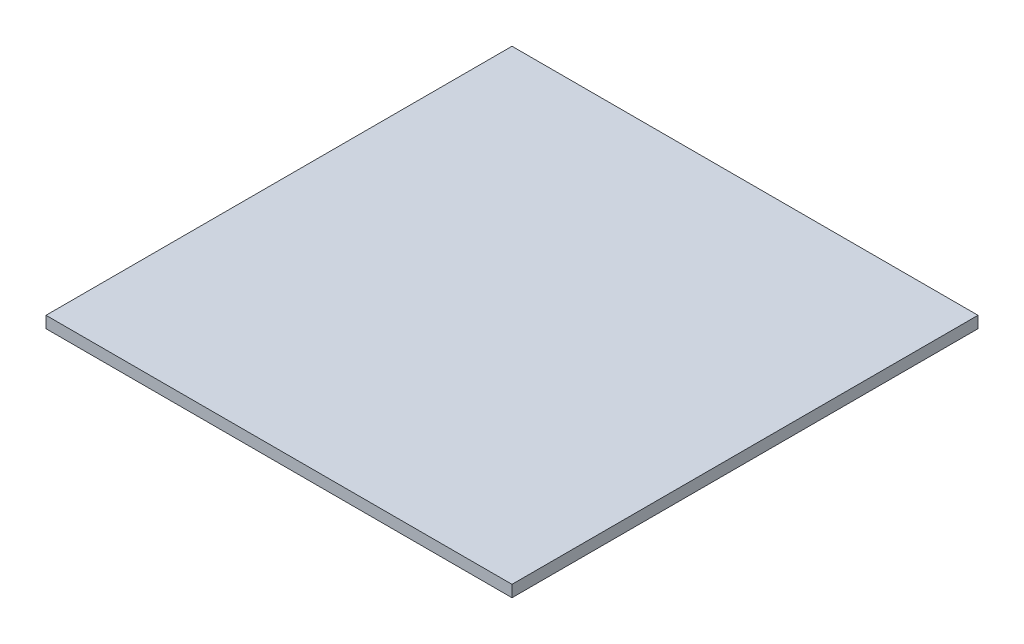
SolidWorks part; units mm, degrees
ref_plane "Front Plane" through (0, 0, 0) normal (0, 0, 1) x (1, 0, 0)
ref_plane "Top Plane" through (0, 0, 0) normal (0, 1, 0) x (1, 0, 0)
ref_plane "Right Plane" through (0, 0, 0) normal (1, 0, 0) x (0, 0, -1)
sketch "Sketch1" plane through (0, 0, 0) normal (0, 1, 0) x (1, 0, 0)
  line L1 (-63.5, -63.5) -> (63.5, -63.5)
  line L2 (-63.5, -63.5) -> (-63.5, 63.5)
  line L3 (-63.5, 63.5) -> (63.5, 63.5)
  line L4 (63.5, -63.5) -> (63.5, 63.5)
  line L5 (-63.5, -63.5) -> (63.5, 63.5) construction
  line L6 (-63.5, 63.5) -> (63.5, -63.5) construction
  point P0 (0, 0)
  dimension "D1" = 127
  dimension "D2" = 127
extrude "Boss-Extrude1" add sketch "Sketch1" along normal blind 3.175
